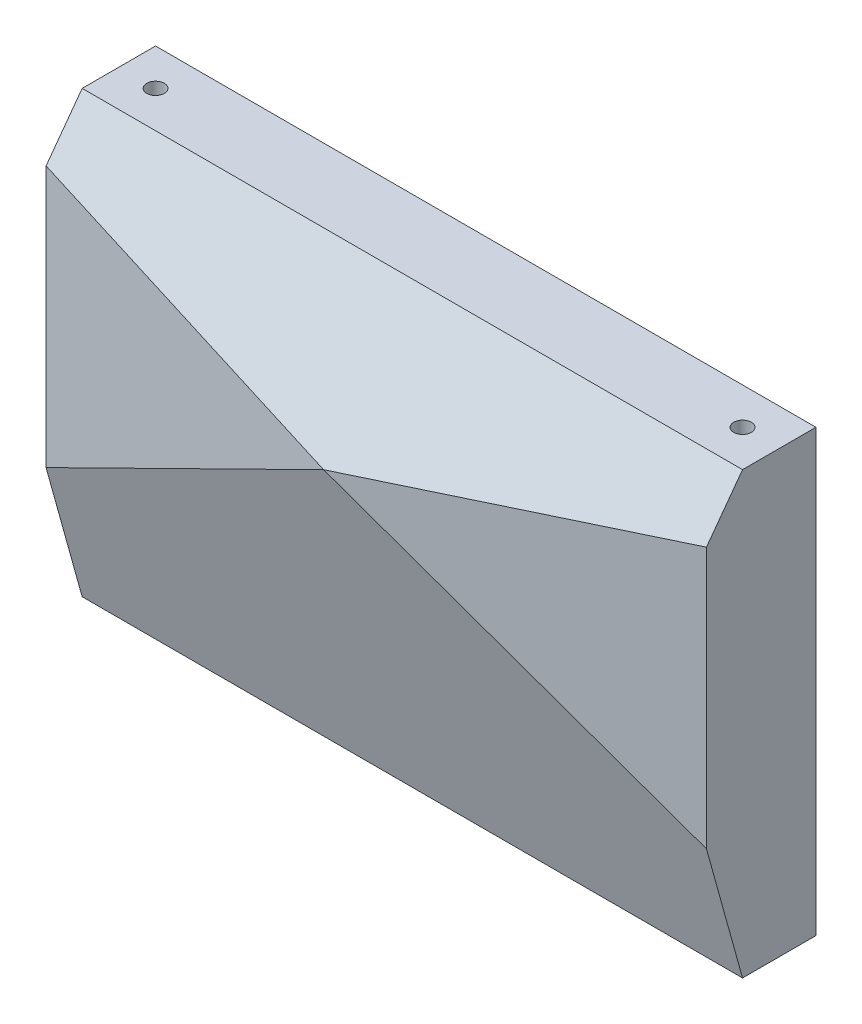
SolidWorks part; units mm, degrees
ref_plane "Ebene vorne" through (0, 0, 0) normal (0, 0, 1) x (1, 0, 0)
ref_plane "Ebene oben" through (0, 0, 0) normal (0, 1, 0) x (1, 0, 0)
ref_plane "Ebene rechts" through (0, 0, 0) normal (1, 0, 0) x (0, 0, -1)
sketch "Skizze1" plane through (0, 0, 0) normal (0, 0, 1) x (1, 0, 0)
  line L1 (0, 0) -> (90, 0)
  line L2 (0, 0) -> (0, 60)
  line L3 (0, 60) -> (90, 60)
  line L4 (90, 0) -> (90, 60)
  dimension "D1" = 90
  dimension "D2" = 60
extrude "Aufsatz-Linear austragen1" add sketch "Skizze1" along normal blind 10
sketch "Skizze2" plane through (0, 0, 10) normal (0, 0, 1) x (1, 0, 0)
  line L0 (10, 50.0503) -> (10, 9.9497)
  line L1 (45, 51.6277) -> (45, -7.4804) construction
  line L2 (13.1837, 51.6625) -> (40.4918, 31.6121)
  line L4 (43.8163, 35.1607) -> (23.0773, 50.3879)
  line L5 (24.261, 54) -> (65.739, 54)
  line L6 (90, 60) -> (0, 60) construction
  line L8 (0, 60) -> (0, 0) construction
  line L9 (-2.0593, 30) -> (95.2495, 30) construction
  line L10 (24.261, 6) -> (65.739, 6)
  line L11 (43.8163, 24.8393) -> (23.0773, 9.6121)
  line L12 (13.1837, 8.3375) -> (40.4918, 28.3879)
  line L13 (46.1837, 35.1607) -> (66.9227, 50.3879)
  line L14 (46.1837, 24.8393) -> (66.9227, 9.6121)
  line L15 (80, 50.0503) -> (80, 9.9497)
  line L16 (76.8163, 8.3375) -> (49.5082, 28.3879)
  line L17 (76.8163, 51.6625) -> (49.5082, 31.6121)
  line L18 (90, 0) -> (90, 60) construction
  arc A0 (80, 9.9497) -> (76.8163, 8.3375) centre (78, 9.9497) cw
  arc A1 (80, 50.0503) -> (76.8163, 51.6625) centre (78, 50.0503) ccw
  arc A2 (49.5082, 28.3879) -> (49.5082, 31.6121) centre (50.6919, 30) cw
  arc A3 (66.9227, 9.6121) -> (65.739, 6) centre (65.739, 8) cw
  arc A4 (24.261, 6) -> (23.0773, 9.6121) centre (24.261, 8) cw
  arc A5 (43.8163, 24.8393) -> (46.1837, 24.8393) centre (45, 23.2271) cw
  arc A6 (66.9227, 50.3879) -> (65.739, 54) centre (65.739, 52) ccw
  arc A7 (43.8163, 35.1607) -> (46.1837, 35.1607) centre (45, 36.7729) ccw
  arc A8 (23.0773, 50.3879) -> (24.261, 54) centre (24.261, 52) cw
  arc A9 (40.4918, 31.6121) -> (40.4918, 28.3879) centre (39.3081, 30) cw
  arc A10 (13.1837, 8.3375) -> (10, 9.9497) centre (12, 9.9497) cw
  arc A11 (10, 50.0503) -> (13.1837, 51.6625) centre (12, 50.0503) cw
  point P19 (10, 30)
  point P20 (45, 54)
  point P21 (45, 6)
  point P30 (80, 6)
  point P33 (80, 54)
  point P36 (47.3126, 30)
  point P39 (71.8423, 6)
  point P42 (18.1577, 6)
  point P45 (45, 25.7083)
  point P48 (71.8423, 54)
  point P51 (45, 34.2917)
  point P54 (18.1577, 54)
  point P57 (42.6874, 30)
  point P60 (10, 6)
  point P63 (10, 54)
  dimension "D5" = 2
  dimension "D1" = 6
  dimension "D2" = 6
  dimension "D3" = 10
  dimension "D4" = 10
extrude "Schnitt-Linear austragen1" cut sketch "Skizze2" against normal blind 10
sketch "Skizze3" plane through (0, 60, 0) normal (0, 1, 0) x (1, 0, 0)
  line L0 (90, -10) -> (90, 0) construction
  line L1 (0, -10) -> (0, 0) construction
  line L2 (90, -10) -> (0, -10) construction
  circle A0 centre (5, -5) radius 1.2
  circle A1 centre (85, -5) radius 1.2
  dimension "D1" = 2.4
  dimension "D2" = 2.4
  dimension "D3" = 5
  dimension "D4" = 5
  dimension "D5" = 5
  dimension "D6" = 5
extrude "Schnitt-Linear austragen2" cut sketch "Skizze3" against normal blind 68
sketch "Skizze4" plane through (90, 0, 0) normal (1, 0, 0) x (0, 0, -1)
  line L0 (-10, 60) -> (-10, 0)
  line L1 (-10, 0) -> (-22.0969, 43.5423)
  line L2 (-22.0969, 43.5423) -> (-10, 60)
  point P1 (-22.0969, 43.5423)
extrude "Aufsatz-Linear austragen2" add sketch "Skizze4" against normal blind 90
sketch "Skizze5" plane through (0, 60, 0) normal (0, 1, 0) x (1, 0, 0)
  line L0 (0, -14.9179) -> (45, -22.0969)
  line L1 (0, -10) -> (0, -22.0969) construction
  line L2 (0, -22.0969) -> (90, -22.0969) construction
  line L3 (45, -22.0969) -> (90, -14.9179)
  line L5 (90, -10) -> (90, -22.0969) construction
  line L6 (90, -14.9179) -> (90, -22.0969)
  line L7 (0, -22.0969) -> (0, -14.9179)
  line L8 (90, -22.0969) -> (0, -22.0969)
extrude "Schnitt-Linear austragen4" cut sketch "Skizze5" against normal blind 90 contours L8 L6 L3 | L8 L0 L7
